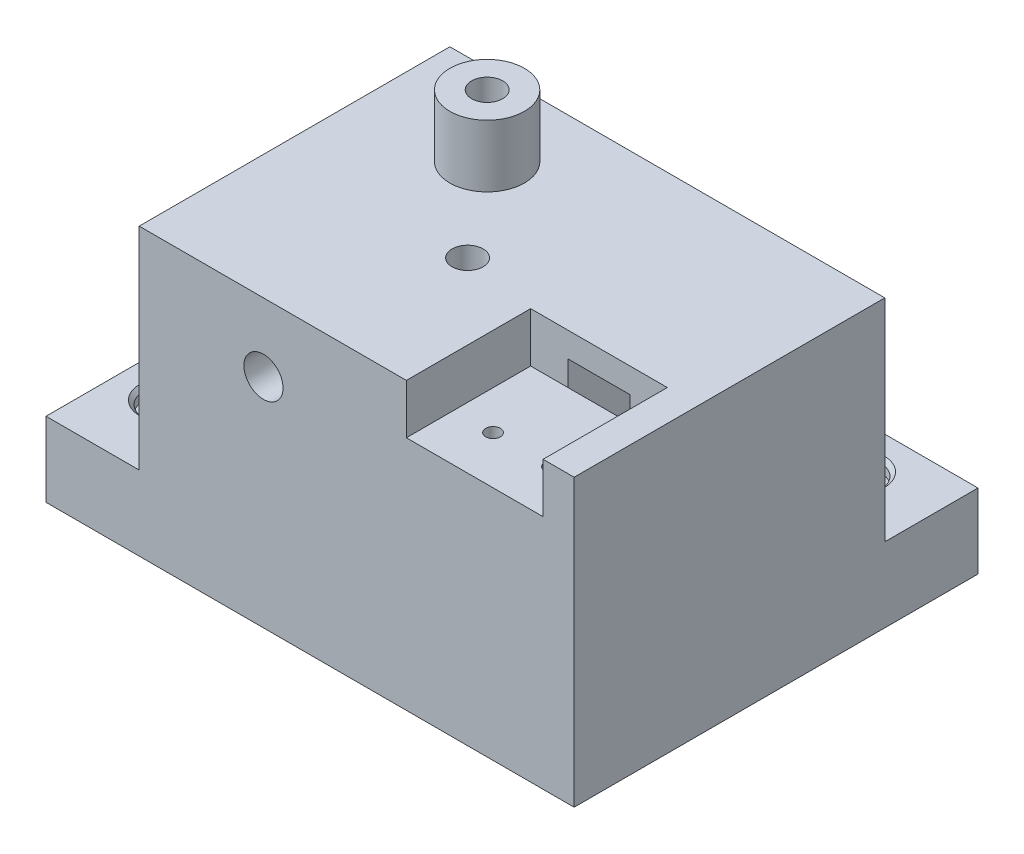
SolidWorks part; units mm, degrees
ref_plane "Front Plane" through (0, 0, 0) normal (0, 0, 1) x (1, 0, 0)
ref_plane "Top Plane" through (0, 0, 0) normal (0, 1, 0) x (1, 0, 0)
ref_plane "Right Plane" through (0, 0, 0) normal (1, 0, 0) x (0, 0, -1)
sketch "Sketch1" plane through (0, 0, 0) normal (0, 1, 0) x (1, 0, 0)
  line L1 (0, 0) -> (70, 0)
  line L2 (0, 0) -> (0, -50)
  line L3 (0, -50) -> (70, -50)
  line L4 (70, 0) -> (70, -50)
  dimension "D1" = 70
  dimension "D2" = 50
extrude "Boss-Extrude1" add sketch "Sketch1" along normal blind 46
sketch "Sketch2" plane through (70, 0, 0) normal (1, 0, 0) x (0, 0, -1)
  line L0 (-50, 46) -> (0, 46) construction
  line L1 (0, 46) -> (0, 0) construction
  circle A0 centre (-25, 35) radius 3.15
  dimension "D1" = 6.3
  dimension "D2" = 11
  dimension "D3" = 25
extrude "Cut-Extrude1" cut sketch "Sketch2" against normal blind 10
sketch "Sketch3" plane through (0, 0, 50) normal (0, 0, 1) x (1, 0, 0)
  line L0 (0, 46) -> (70, 46) construction
  line L1 (0, 46) -> (0, 0) construction
  circle A0 centre (20, 35) radius 3.15
  dimension "D3" = 6.3
  dimension "D1" = 11
  dimension "D2" = 20
extrude "Cut-Extrude2" cut sketch "Sketch3" against normal blind 30
sketch "Sketch4" plane through (0, 46, 0) normal (0, 1, 0) x (1, 0, 0)
  line L0 (70, -50) -> (70, 0) construction
  line L1 (0, -50) -> (70, -50) construction
  line L2 (70, 0) -> (0, 0) construction
  circle A0 centre (30.85, -28) radius 2.5
  circle A1 centre (19, -13) radius 2.5
  dimension "D3" = 5
  dimension "D6" = 5
  dimension "D1" = 39.15
  dimension "D2" = 22
  dimension "D4" = 51
  dimension "D5" = 13
extrude "Cut-Extrude3" cut sketch "Sketch4" against normal blind 10
sketch "Sketch5" plane through (0, 0, 0) normal (-1, 0, 0) x (0, 0, 1)
  line L0 (0, 12) -> (50, 12) construction
  line L1 (0, 46) -> (0, 0) construction
  line L2 (50, 46) -> (50, 0) construction
  line L3 (0, 0) -> (50, 0) construction
  line L5 (0, 0) -> (50, 0)
  line L6 (0, 0) -> (0, 12)
  line L7 (0, 12) -> (50, 12)
  line L8 (50, 0) -> (50, 12)
  dimension "D1" = 12
extrude "Boss-Extrude2" add sketch "Sketch5" along normal blind 15
sketch "Sketch8" plane through (0, 0, 0) normal (0, 0, -1) x (-1, 0, 0)
  line L0 (15, 12) -> (-70, 12) construction
  line L1 (-70, 46) -> (-70, 0) construction
  line L3 (-70, 0) -> (15, 0)
  line L4 (-70, 0) -> (-70, 12)
  line L5 (-70, 12) -> (15, 12)
  line L6 (15, 0) -> (15, 12)
extrude "Boss-Extrude5" add sketch "Sketch8" along normal blind 15
hole_wizard "CBORE for #5 Binding Head Machine Screw2" positions "Sketch10" profile "Sketch11" counterbore size "#5" standard "ANSI Inch" end condition through all
sketch "Sketch10" plane through (0, 12, 0) normal (0, 1, 0) x (1, 0, 0)
  line L0 (0, 0) -> (-15, 15) construction
  line L2 (70, 15) -> (70, 0) construction
  line L3 (-15, -50) -> (0, -50) construction
  circle A0 centre (-7.5, 7.5) radius 2.4945
  circle A1 centre (58, 7.5) radius 2.3741
  circle A2 centre (-7.5, -38) radius 2.972
  point P6 (-7.5, 7.5)
  point P9 (58, 7.5)
  point P13 (-7.5, -38)
  dimension "D1" = 12
  dimension "D2" = 12
sketch "Sketch11" plane through (-7.5, 12, 38) normal (1, 0, 0) x (0, 0, 1)
  line L0 (0, 0) -> (0, 12)
  line L1 (0, 12) -> (1.7272, 12)
  line L3 (1.7272, 12) -> (1.7272, 1.9812)
  line L4 (3.7706, 1.9812) -> (1.7272, 1.9812)
  line L5 (3.7706, 1.9812) -> (3.7706, 0.635)
  line L6 (3.7706, 0.635) -> (4.4056, 0)
  line L7 (4.4056, 0) -> (0, 0)
  line L8 (-3.7706, 0.635) -> (-4.4056, 0) construction
  line L11 (0, -6.35) -> (0, 107.95) construction
  dimension "Thru Hole Dia." = 3.4544
  dimension "Thru Hole Depth" = 12
  dimension "C'Bore Dia." = 7.5413
  dimension "C'Bore Depth" = 1.9812
  dimension "Near C'Sink Dia." = 8.8113
  dimension "Near C'Sink Angle" = 90
sketch "Sketch12" plane through (70, 0, 0) normal (1, 0, 0) x (0, 0, -1)
  circle A0 centre (-25, 35) radius 3.15
extrude "Boss-Extrude6" add sketch "Sketch12" against normal blind 10
sketch "Sketch13" plane through (0, 46, 0) normal (0, 1, 0) x (1, 0, 0)
  circle A0 centre (19, -13) radius 6
  circle A1 centre (19, -13) radius 2.5
  dimension "D1" = 12
extrude "Boss-Extrude7" add sketch "Sketch13" along normal blind 10
sketch "Sketch14" plane through (0, 0, 50) normal (0, 0, 1) x (1, 0, 0)
  line L0 (0, 46) -> (70, 46) construction
  line L1 (43, 46) -> (65, 46)
  line L2 (43, 46) -> (43, 38)
  line L3 (43, 38) -> (65, 38)
  line L4 (65, 46) -> (65, 38)
  line L5 (70, 46) -> (70, 0) construction
  dimension "D1" = 22
  dimension "D2" = 5
  dimension "D3" = 8
extrude "Cut-Extrude4" cut sketch "Sketch14" against normal blind 20
sketch "Sketch15" plane through (0, 38, 0) normal (0, 1, 0) x (1, 0, 0)
  line L0 (43, -50) -> (65, -50) construction
  line L1 (54, -50) -> (54, -30) construction
  line L2 (65, -30) -> (43, -30) construction
  circle A0 centre (49.25, -42.3) radius 1.185
  circle A1 centre (58.75, -42.3) radius 1.185
  dimension "D1" = 2.37
  dimension "D2" = 2.37
  dimension "D3" = 7.7
  dimension "D4" = 7.7
  dimension "D5" = 4.75
  dimension "D6" = 4.75
extrude "Cut-Extrude5" cut sketch "Sketch15" against normal blind 10
sketch "Sketch16" plane through (0, 0, 30) normal (0, 0, 1) x (1, 0, 0)
  line L0 (54, 46) -> (54, 38) construction
  line L1 (65, 46) -> (43, 46) construction
  line L2 (43, 38) -> (65, 38) construction
  line L3 (54, 42) -> (59, 42)
  line L4 (59, 42) -> (59, 38)
  line L5 (59, 38) -> (49, 38)
  line L6 (49, 38) -> (49, 42)
  line L7 (49, 42) -> (54, 42)
  dimension "D1" = 5
  dimension "D2" = 5
  dimension "D3" = 4
extrude "Cut-Extrude6" cut sketch "Sketch16" against normal blind 10
sketch "Sketch17" plane through (0, 38, 0) normal (0, 1, 0) x (1, 0, 0)
  line L0 (49, -30) -> (59, -30)
  line L1 (59, -30) -> (59, -20)
  line L2 (59, -20) -> (49, -20)
  line L3 (49, -20) -> (49, -30)
  dimension "D1" = 10
extrude "Cut-Extrude7" cut sketch "Sketch17" against normal blind 63
sketch "Sketch18" plane through (0, 0, 0) normal (0, 0, -1) x (-1, 0, 0)
  text T0 "29"
extrude "Cut-Extrude8" cut sketch "Sketch18" against normal blind 2
